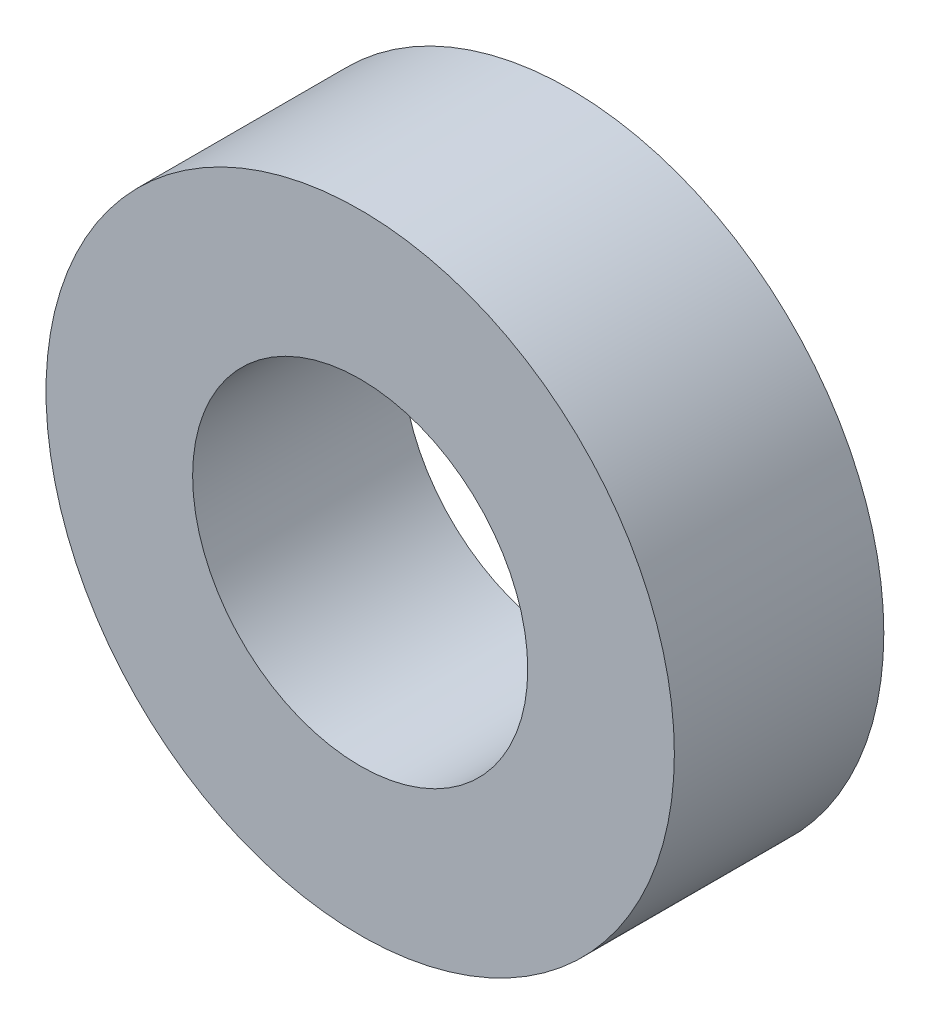
SolidWorks part; units mm, degrees
ref_plane "Front Plane" through (0, 0, 0) normal (0, 0, 1) x (1, 0, 0)
ref_plane "Top Plane" through (0, 0, 0) normal (0, 1, 0) x (1, 0, 0)
ref_plane "Right Plane" through (0, 0, 0) normal (1, 0, 0) x (0, 0, -1)
sketch "Sketch1" plane through (0, 0, 0) normal (0, 0, 1) x (1, 0, 0)
  circle A0 centre (0, 0) radius 4
  circle A1 centre (0, 0) radius 7.5
  dimension "D1" = 8
  dimension "D2" = 15
extrude "Boss-Extrude1" add sketch "Sketch1" along normal blind 5
